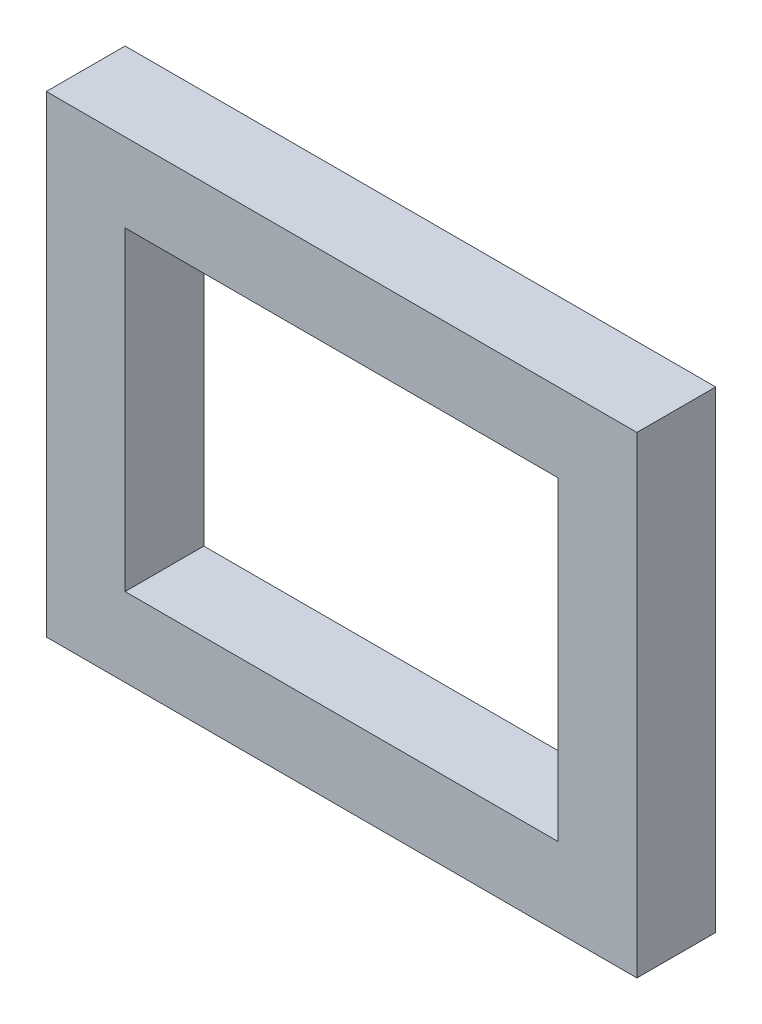
SolidWorks part; units mm, degrees
ref_plane "Front Plane" through (0, 0, 0) normal (0, 0, 1) x (1, 0, 0)
ref_plane "Top Plane" through (0, 0, 0) normal (0, 1, 0) x (1, 0, 0)
ref_plane "Right Plane" through (0, 0, 0) normal (1, 0, 0) x (0, 0, -1)
sketch "Sketch1" plane through (0, 0, 0) normal (0, 0, 1) x (1, 0, 0)
  line L1 (-37.5, -30) -> (37.5, -30)
  line L2 (-37.5, -30) -> (-37.5, 30)
  line L3 (-37.5, 30) -> (37.5, 30)
  line L4 (37.5, -30) -> (37.5, 30)
  line L5 (-37.5, -30) -> (37.5, 30) construction
  line L6 (-37.5, 30) -> (37.5, -30) construction
  line L7 (-27.5, -20) -> (27.5, -20)
  line L8 (-27.5, -20) -> (-27.5, 20)
  line L9 (-27.5, 20) -> (27.5, 20)
  line L10 (27.5, -20) -> (27.5, 20)
  line L11 (-27.5, -20) -> (27.5, 20) construction
  line L12 (-27.5, 20) -> (27.5, -20) construction
  point P0 (0, 0)
  point P6 (0, 0)
  point P11 (37.5, 37.5)
  point P12 (0, 0)
  point P13 (27.5, 10.3524)
  dimension "D1" = 75
  dimension "D2" = 10
  dimension "D3" = 10
  dimension "D4" = 60
extrude "Boss-Extrude1" add sketch "Sketch1" along normal blind 10
